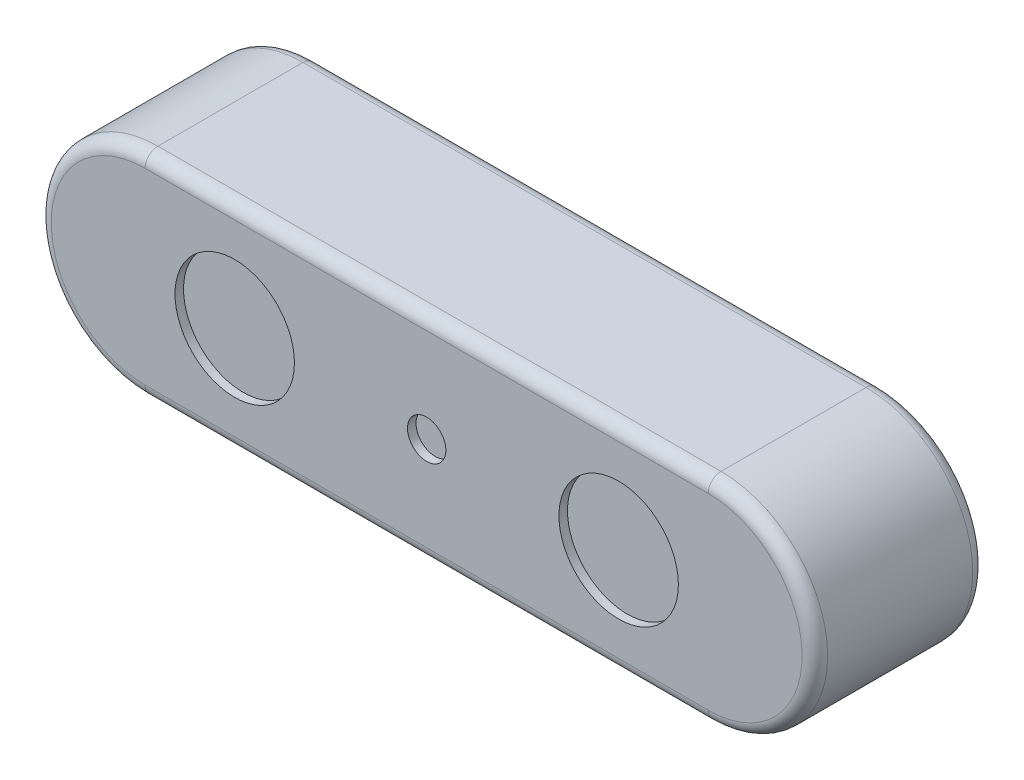
SolidWorks part; units mm, degrees
ref_plane "Front Plane" through (0, 0, 0) normal (0, 0, 1) x (1, 0, 0)
ref_plane "Top Plane" through (0, 0, 0) normal (0, 1, 0) x (1, 0, 0)
ref_plane "Right Plane" through (0, 0, 0) normal (1, 0, 0) x (0, 0, -1)
sketch "Sketch1" plane through (0, 0, 0) normal (0, 0, 1) x (1, 0, 0)
  line L1 (-33, 12.5) -> (33, 12.5)
  line L3 (-33, -12.5) -> (33, -12.5)
  arc A0 (33, -12.5) -> (33, 12.5) centre (33, 0) ccw
  arc A1 (-33, 12.5) -> (-33, -12.5) centre (-33, 0) ccw
  point P0 (0, 0)
  dimension "D1" = 66
  dimension "D2" = 25
extrude "Boss-Extrude1" add sketch "Sketch1" along normal blind 20
fillet "Fillet1" radius 1.5 8 edges at (45.5, 0, 20) (0, -12.5, 20) (-45.5, 0, 20) (0, 12.5, 20) (45.5, 0, 0) (0, -12.5, 0) (-45.5, 0, 0) (0, 12.5, 0)
sketch "Sketch2" plane through (0, 0, 20) normal (0, 0, 1) x (1, 0, 0)
  line L0 (-22.5, 0) -> (22.5, 0) construction
  circle A0 centre (-22.5, 0) radius 7
  circle A1 centre (22.5, 0) radius 7
  circle A2 centre (0, 0) radius 2.25
  point P4 (0, 0)
  dimension "D1" = 45
extrude "Cut-Extrude1" cut sketch "Sketch2" against normal blind 1
sketch "Sketch3" plane through (0, -12.5, 0) normal (0, -1, 0) x (1, 0, 0)
  line L1 (-33, 20) -> (33, 20) construction
  line L2 (-45.5, 18.5) -> (-45.5, 1.5) construction
  circle A0 centre (-17.5, 10) radius 1.5
  circle A1 centre (16.5, 10) radius 1.5
  dimension "D1" = 3
  dimension "D2" = 10
  dimension "D3" = 28
  dimension "D4" = 34
extrude "Cut-Extrude2" cut sketch "Sketch3" against normal blind 3
